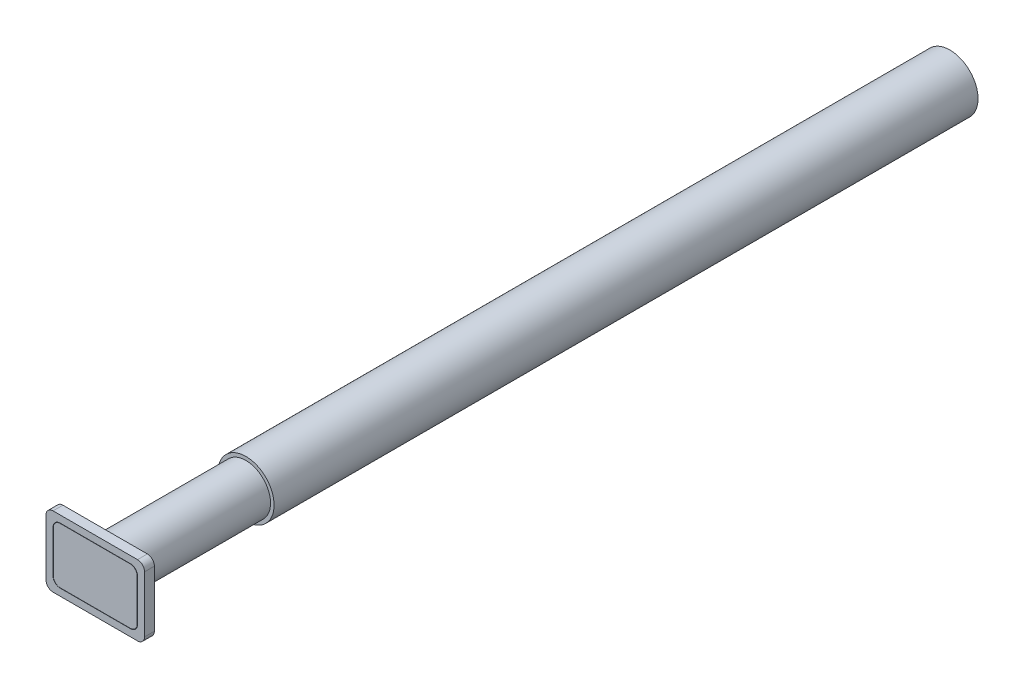
SolidWorks part; units mm, degrees
ref_plane "Front Plane" through (0, 0, 0) normal (0, 0, 1) x (1, 0, 0)
ref_plane "Top Plane" through (0, 0, 0) normal (0, 1, 0) x (1, 0, 0)
ref_plane "Right Plane" through (0, 0, 0) normal (1, 0, 0) x (0, 0, -1)
sketch "Sketch1" plane through (0, 0, 0) normal (0, 0, 1) x (1, 0, 0)
  circle A0 centre (0, 0) radius 25.4
  dimension "D1" = 50.8
extrude "Boss-Extrude1" add sketch "Sketch1" along normal blind 635
sketch "Sketch2" plane through (0, 0, 635) normal (0, 0, 1) x (1, 0, 0)
  circle A0 centre (0, 0) radius 22.225
  dimension "D1" = 44.45
extrude "Boss-Extrude2" add sketch "Sketch2" along normal blind 127
sketch "Sketch3" plane through (0, 0, 762) normal (0, 0, 1) x (1, 0, 0)
  line L1 (-38.1, 31.75) -> (38.1, 31.75)
  line L2 (-44.45, 25.4) -> (-44.45, -25.4)
  line L3 (-38.1, -31.75) -> (38.1, -31.75)
  line L4 (44.45, 25.4) -> (44.45, -25.4)
  arc A0 (38.1, 31.75) -> (44.45, 25.4) centre (38.1, 25.4) cw
  arc A1 (38.1, -31.75) -> (44.45, -25.4) centre (38.1, -25.4) ccw
  arc A2 (-44.45, -25.4) -> (-38.1, -31.75) centre (-38.1, -25.4) ccw
  arc A3 (-38.1, 31.75) -> (-44.45, 25.4) centre (-38.1, 25.4) ccw
  point P7 (44.45, 31.75)
  point P10 (44.45, -31.75)
  point P15 (-44.45, 31.75)
  dimension "D5" = 6.35
  dimension "D1" = 88.9
  dimension "D2" = 63.5
  dimension "D3" = 44.45
  dimension "D4" = 31.75
extrude "Boss-Extrude3" add sketch "Sketch3" along normal blind 8.89
sketch "Sketch4" plane through (0, 0, 770.89) normal (0, 0, 1) x (1, 0, 0)
  line L1 (-31.75, -25.4) -> (31.75, -25.4)
  line L2 (-38.1, -19.05) -> (-38.1, 19.05)
  line L3 (-31.75, 25.4) -> (31.75, 25.4)
  line L4 (38.1, -19.05) -> (38.1, 19.05)
  arc A0 (31.75, 25.4) -> (38.1, 19.05) centre (31.75, 19.05) cw
  arc A1 (31.75, -25.4) -> (38.1, -19.05) centre (31.75, -19.05) ccw
  arc A2 (-31.75, -25.4) -> (-38.1, -19.05) centre (-31.75, -19.05) cw
  arc A3 (-38.1, 19.05) -> (-31.75, 25.4) centre (-31.75, 19.05) cw
  point P8 (38.1, 25.4)
  point P11 (38.1, -25.4)
  point P16 (-38.1, 25.4)
  dimension "D5" = 6.35
  dimension "D1" = 76.2
  dimension "D2" = 50.8
  dimension "D3" = 25.4
  dimension "D4" = 38.1
extrude "Cut-Extrude1" cut sketch "Sketch4" against normal blind 6.35
ref_plane "Plane1" through (0, 0, 764.794) normal (0, 0, 1) x (1, 0, 0)
sketch "Sketch5" plane through (0, 0, 764.794) normal (0, 0, 1) x (1, 0, 0)
  line L1 (-31.496, 25.146) -> (31.496, 25.146)
  line L2 (-37.846, 18.796) -> (-37.846, -18.796)
  line L3 (-31.496, -25.146) -> (31.496, -25.146)
  line L4 (37.846, 18.796) -> (37.846, -18.796)
  arc A0 (31.496, 25.146) -> (37.846, 18.796) centre (31.496, 18.796) cw
  arc A1 (31.496, -25.146) -> (37.846, -18.796) centre (31.496, -18.796) ccw
  arc A2 (-37.846, -18.796) -> (-31.496, -25.146) centre (-31.496, -18.796) ccw
  arc A3 (-31.496, 25.146) -> (-37.846, 18.796) centre (-31.496, 18.796) ccw
  point P8 (37.846, 25.146)
  point P13 (-37.846, -25.146)
  point P16 (-37.846, 25.146)
  dimension "D5" = 6.35
  dimension "D1" = 75.692
  dimension "D2" = 50.292
  dimension "D3" = 37.846
  dimension "D4" = 25.146
extrude "Boss-Extrude5" add sketch "Sketch5" along normal blind 6.096 separate body
